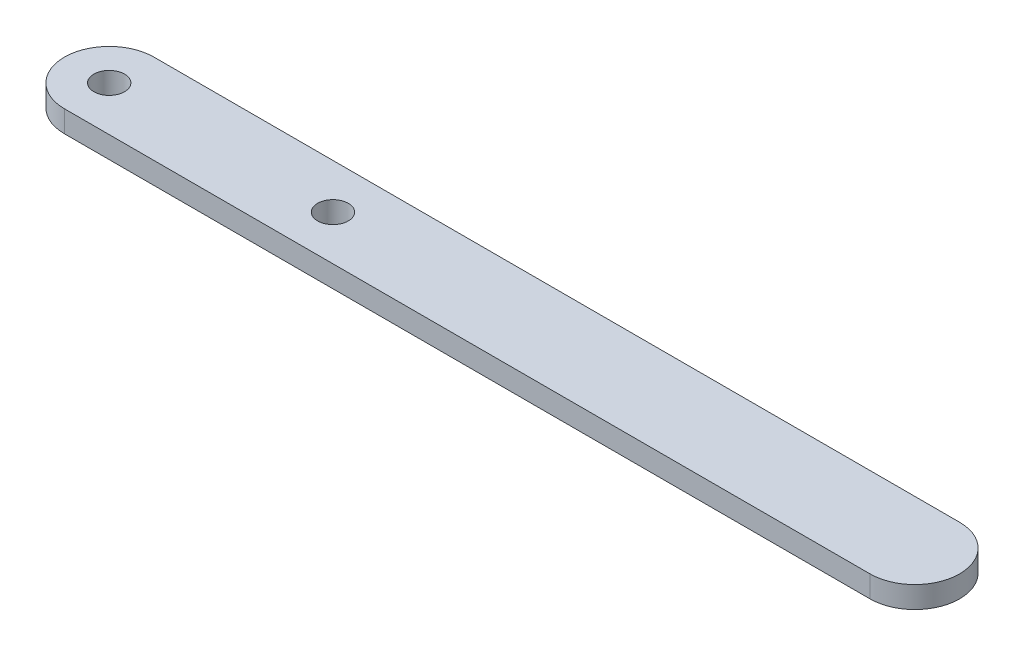
SolidWorks part; units mm, degrees
material "PET"
ref_plane "Front" through (0, 0, 0) normal (0, 0, 1) x (1, 0, 0)
ref_plane "Top" through (0, 0, 0) normal (0, 1, 0) x (1, 0, 0)
ref_plane "Right" through (0, 0, 0) normal (1, 0, 0) x (0, 0, -1)
sketch "Sketch1" plane through (0, 0, 0) normal (0, 1, 0) x (1, 0, 0)
  line L1 (-100.9447, 8.7002) -> (13.3553, 8.7002)
  line L3 (-100.9447, -3.9998) -> (13.3553, -3.9998)
  line L5 (-100.9447, 8.7002) -> (13.3553, -3.9998) construction
  line L6 (-100.9447, -3.9998) -> (13.3553, 8.7002) construction
  arc A0 (-100.9447, 8.7002) -> (-100.9447, -3.9998) centre (-100.9447, 2.3502) ccw
  arc A2 (13.3553, 8.7002) -> (13.3553, -3.9998) centre (13.3553, 2.3502) cw
  point P4 (-43.7947, 2.3502)
  dimension "D1" = 114.3
  dimension "D2" = 12.7
extrude "Boss-Extrude1" add sketch "Sketch1" along normal blind 3.075
sketch "Sketch2" plane through (0, 3.075, 0) normal (0, 1, 0) x (1, 0, 0)
  circle A0 centre (-100.9447, 2.3502) radius 2.175
  circle A1 centre (-69.1947, 2.3502) radius 2.175
  dimension "D1" = 31.75
  dimension "D2" = 4.35
  dimension "D3" = 4.35
extrude "Cut-Extrude2" cut sketch "Sketch2" against normal blind 6.35
